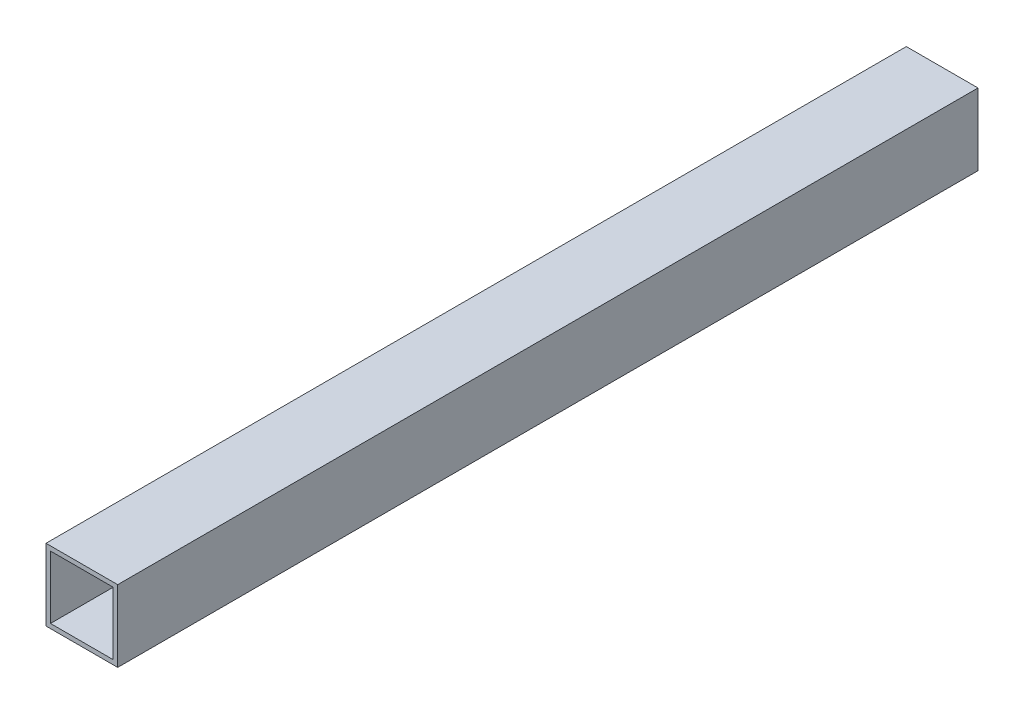
SolidWorks part; units mm, degrees
ref_plane "Front Plane" through (0, 0, 0) normal (0, 0, 1) x (1, 0, 0)
ref_plane "Top Plane" through (0, 0, 0) normal (0, 1, 0) x (1, 0, 0)
ref_plane "Right Plane" through (0, 0, 0) normal (1, 0, 0) x (0, 0, -1)
sketch "Sketch1" plane through (0, 0, 0) normal (0, 0, 1) x (1, 0, 0)
  line L0 (12.7, 0) -> (11.1125, 0) construction
  line L1 (-12.7, 0) -> (12.7, 0) construction
  line L2 (0, 12.7) -> (0, -12.7)
  point P7 (0, 0)
sketch "Sketch2" plane through (0, 0, 0) normal (1, 0, 0) x (0, 0, -1)
  line L0 (914.4, 0) -> (-914.4, 0)
  point P4 (0, 0)
  dimension "Length" = 1828.8
sketch "Sketch3" plane through (0, 0, 0) normal (0, 0, 1) x (1, 0, 0)
  line L5 (-12.7, -12.7) -> (12.7, -12.7)
  line L11 (-12.7, -12.7) -> (-12.7, 12.7)
  line L12 (-12.7, 12.7) -> (12.7, 12.7)
  line L13 (-11.1125, -11.1125) -> (11.1125, -11.1125)
  line L14 (12.7, -12.7) -> (12.7, 12.7)
  line L18 (-12.7, -12.7) -> (12.7, 12.7) construction
  line L19 (-12.7, 12.7) -> (12.7, -12.7) construction
  line L20 (-11.1125, -11.1125) -> (-11.1125, 11.1125)
  line L21 (-11.1125, 11.1125) -> (11.1125, 11.1125)
  line L22 (11.1125, -11.1125) -> (11.1125, 11.1125)
  line L23 (-11.1125, -11.1125) -> (11.1125, 11.1125) construction
  line L24 (-11.1125, 11.1125) -> (11.1125, -11.1125) construction
  point P0 (0, 0)
  point P1 (0, 0)
  point P10 (11.1125, -12.7)
  dimension "D2" = 1.5875
  dimension "D3" = 25.4
  dimension "D4" = 25.4
  dimension "D1" = 1.5875
extrude "Boss-Extrude1" add sketch "Sketch3" along normal up to vertex (914.4 mm away) and the other way up to vertex (914.4 mm away) up to point (0, 0, 914.4) other way up to point (0, 0, -914.4)
sketch "Sketch4" plane through (0, 0, 0) normal (1, 0, 0) x (0, 0, -1)
  line L0 (914.4, 0) -> (-914.4, 0) construction
  line L1 (-914.4, -12.7) -> (-914.4, 12.7) construction
  point P0 (-885.825, 0)
  point P6 (0, 0)
  point P8 (-876.3, 0)
  point P9 (876.3, 0)
  point P10 (885.825, 0)
  dimension "D1" = 28.575
  dimension "D2" = 38.1
  dimension "D3" = 28.575
  dimension "D4" = 38.1
sketch "Sketch5" plane through (0, 0, 914.4) normal (0, 0, 1) x (1, 0, 0)
  line L1 (-32.7767, -35.0682) -> (32.7767, -35.0682)
  line L2 (-32.7767, -35.0682) -> (-32.7767, 35.0682)
  line L3 (-32.7767, 35.0682) -> (32.7767, 35.0682)
  line L4 (32.7767, -35.0682) -> (32.7767, 35.0682)
  line L5 (-32.7767, -35.0682) -> (32.7767, 35.0682) construction
  line L6 (-32.7767, 35.0682) -> (32.7767, -35.0682) construction
  point P0 (0, 0)
extrude "Cut-Extrude1" cut sketch "Sketch5" against normal blind 1524
equation "\"D2@Sketch3\"=\"Wall Thickness@Sketch1\""
equation "\"D1@Sketch4\"=\"Width@Sketch1\"*1.125"
equation "\"D2@Sketch4\"=\"Width@Sketch1\"*1.5"
equation "\"D3@Sketch4\"=\"D1@Sketch4\""
equation "\"D4@Sketch4\"=\"D2@Sketch4\""
